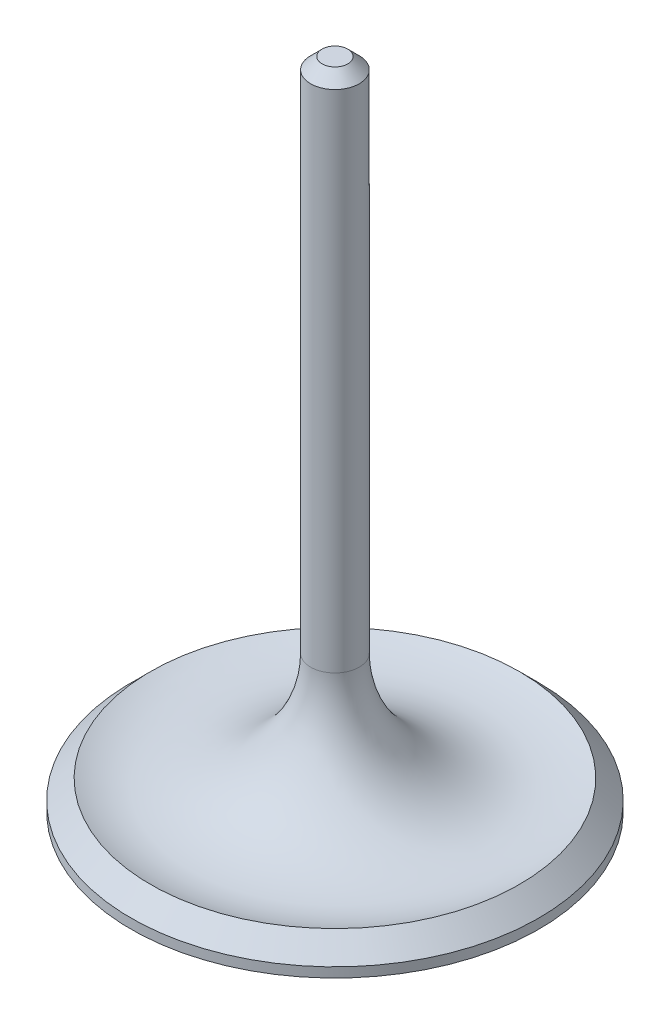
SolidWorks part; units mm, degrees
ref_plane "Front Plane" through (0, 0, 0) normal (0, 0, 1) x (1, 0, 0)
ref_plane "Top Plane" through (0, 0, 0) normal (0, 1, 0) x (1, 0, 0)
ref_plane "Right Plane" through (0, 0, 0) normal (1, 0, 0) x (0, 0, -1)
sketch "Sketch1" plane through (0, 0, 0) normal (0, 0, 1) x (1, 0, 0)
  line L0 (0, 0) -> (0, 85.55)
  line L1 (0, 85.55) -> (3.18, 85.55)
  line L2 (3.18, 85.55) -> (3.18, 17.9547)
  line L3 (24.13, 3.81) -> (26.67, 1.27)
  line L4 (26.67, 1.27) -> (26.67, 0)
  line L5 (26.67, 0) -> (0, 0)
  arc A0 (3.18, 17.9547) -> (24.13, 3.81) centre (18.43, 17.9547) ccw
  dimension "D1" = 85.55
  dimension "D7" = 15.25
  dimension "D2" = 26.67
  dimension "D3" = 3.18
  dimension "D4" = 1.27
  dimension "D5" = 3.81
  dimension "D6" = 45
revolve "Revolve1" add sketch "Sketch1" angle 360 about L0
chamfer "Chamfer1" distance 1.5 angle 45 1 edges at (0, 85.55, -3.18)
